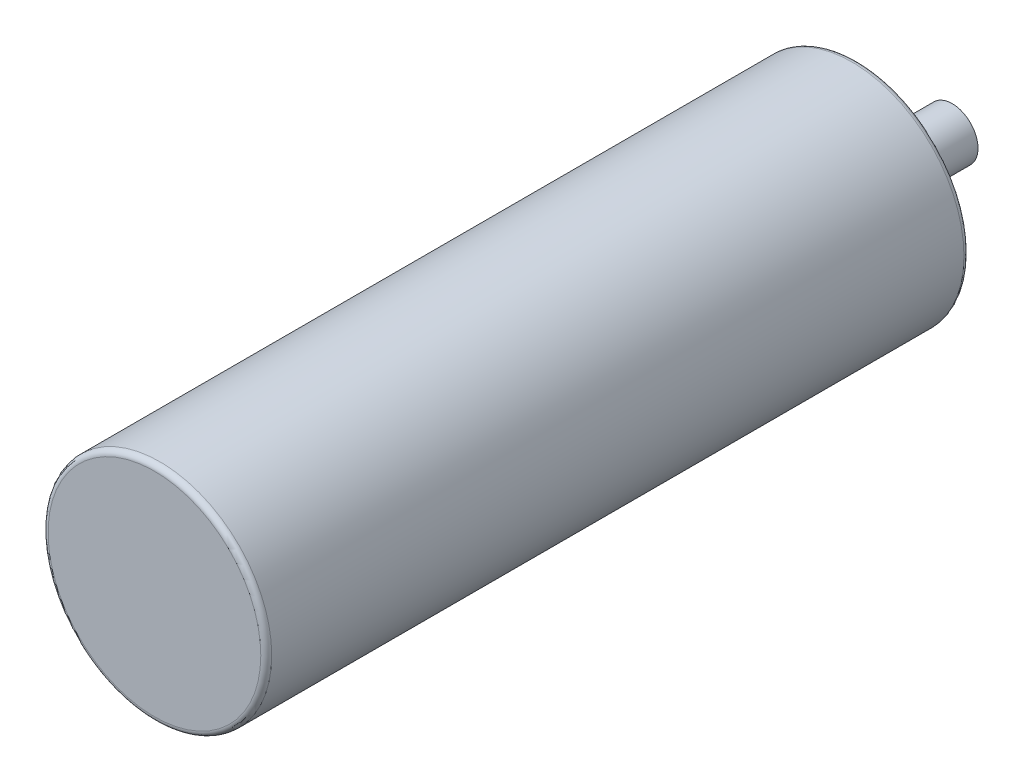
SolidWorks part; units mm, degrees
ref_plane "Front Plane" through (0, 0, 0) normal (0, 0, 1) x (1, 0, 0)
ref_plane "Top Plane" through (0, 0, 0) normal (0, 1, 0) x (1, 0, 0)
ref_plane "Right Plane" through (0, 0, 0) normal (1, 0, 0) x (0, 0, -1)
sketch "Sketch1" plane through (0, 0, 0) normal (0, 0, 1) x (1, 0, 0)
  circle A0 centre (0, 0) radius 26
  dimension "D1" = 52
extrude "body" add sketch "Sketch1" along normal blind 163.5
sketch "Sketch2" plane through (0, 0, 0) normal (0, 0, -1) x (-1, 0, 0)
  circle A0 centre (0, 0) radius 6
  dimension "D1" = 12
extrude "axle" add sketch "Sketch2" along normal blind 22
sketch "Sketch3" plane through (0, 0, -22) normal (0, 0, -1) x (-1, 0, 0)
  line L0 (-4.4721, -4) -> (4.4721, -4)
  circle A0 centre (0, 0) radius 6 construction
  circle A1 centre (0, 0) radius 6
  circle A2 centre (0, 0) radius 1.016
  point P5 (0, 6)
  circle M2 centre (0, 0) radius 6
  dimension "D1" = 2.032
  dimension "D2" = 10
extrude "flat" cut sketch "Sketch3" against normal blind 15 contours L0 M2 | A2
hole_wizard "M5x0.8 Tapped Hole1" positions "Sketch6" profile "Sketch7" tap size "M5x0.8" standard "ANSI Metric"
sketch "Sketch6" plane through (0, 0, 0) normal (0, 0, -1) x (-1, 0, 0)
  circle A0 centre (0, 0) radius 20
  point P5 (0, -20)
  point P7 (-20, 0)
  point P9 (0, 20)
  point P11 (20, 0)
  dimension "D1" = 40
sketch "Sketch7" plane through (0, -20, 0) normal (1, 0, 0) x (0, 1, 0)
  line L0 (0, 0) -> (0, 33.2618)
  line L1 (0, 33.2618) -> (2.1, 32)
  line L2 (2.1, 32) -> (2.1, 0)
  line L5 (2.1, 0) -> (0, 0)
  line L10 (0, 33.2618) -> (-2.1, 32) construction
  line L11 (0, -6.35) -> (0, 107.95) construction
  dimension "Tap Drill Dia." = 4.2
  dimension "Tap Drill Depth" = 32
  dimension "Drill Angle" = 118
cosmetic thread "Hole Thread1" parameters "D1"=0.254, "D2"=5
cosmetic thread "Hole Thread2" parameters "D1"=0.254, "D2"=5
cosmetic thread "Hole Thread3" parameters "D1"=0.254, "D2"=5
cosmetic thread "Hole Thread4" parameters "D1"=0.254, "D2"=5
fillet "Fillet1" radius 1.27 2 edges at (26, 0, 0) (26, 0, 163.5)
